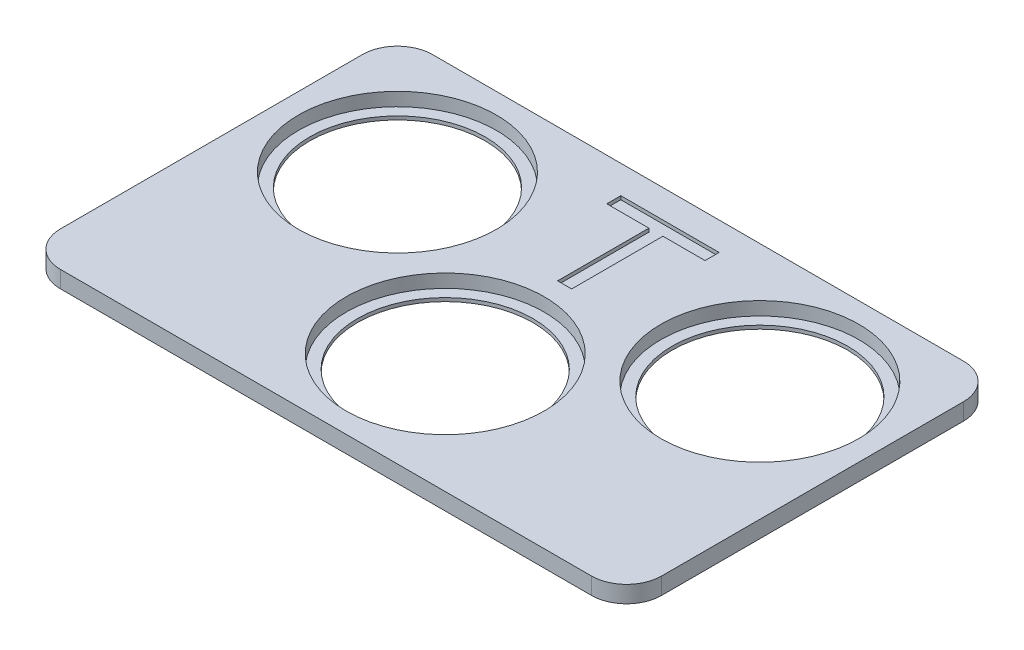
SolidWorks part; units mm, degrees
ref_plane "Front Plane" through (0, 0, 0) normal (0, 0, 1) x (1, 0, 0)
ref_plane "Top Plane" through (0, 0, 0) normal (0, 1, 0) x (1, 0, 0)
ref_plane "Right Plane" through (0, 0, 0) normal (1, 0, 0) x (0, 0, -1)
sketch "Sketch1" plane through (0, 0, 0) normal (0, 1, 0) x (1, 0, 0)
  line L1 (-42.8, 26.49) -> (42.8, 26.49)
  line L2 (-42.8, 26.49) -> (-42.8, -26.49)
  line L3 (-42.8, -26.49) -> (42.8, -26.49)
  line L4 (42.8, 26.49) -> (42.8, -26.49)
  line L5 (-42.8, 26.49) -> (42.8, -26.49) construction
  line L6 (-42.8, -26.49) -> (42.8, 26.49) construction
  point P0 (0, 0)
  dimension "D1" = 85.6
  dimension "D2" = 52.98
extrude "Boss-Extrude1" add sketch "Sketch1" along normal blind 2.4
sketch "Sketch2" plane through (0, 2.4, 0) normal (0, 1, 0) x (1, 0, 0)
  line L0 (-42.8, 26.49) -> (-42.8, -26.49) construction
  line L1 (42.8, 26.49) -> (-42.8, 26.49) construction
  line L2 (42.8, -26.49) -> (42.8, 26.49) construction
  circle A0 centre (-25.8, 9.49) radius 14.1
  circle A1 centre (0, -9.51) radius 14.1
  circle A2 centre (25.8, 9.49) radius 14.1
  dimension "D1" = 28.2
  dimension "D2" = 28.2
  dimension "D3" = 28.2
  dimension "D4" = 17
  dimension "D5" = 17
  dimension "D6" = 17
  dimension "D7" = 19
extrude "Cut-Extrude1" cut sketch "Sketch2" against normal blind 1.9
sketch "Sketch3" plane through (0, 0.5, 0) normal (0, 1, 0) x (1, 0, 0)
  circle A0 centre (-25.8, 9.49) radius 12.5
  circle A1 centre (0, -9.51) radius 12.5
  circle A2 centre (25.8, 9.49) radius 12.5
  dimension "D1" = 25
  dimension "D2" = 25
  dimension "D3" = 25
extrude "Cut-Extrude2" cut sketch "Sketch3" against normal blind 1.75
fillet "Fillet1" radius 5 4 edges at (42.8, 1.2, -26.49) (42.8, 1.2, 26.49) (-42.8, 1.2, 26.49) (-42.8, 1.2, -26.49)
sketch "Sketch4" plane through (0, 2.4, 0) normal (0, 1, 0) x (1, 0, 0)
  line L0 (-1, 20.49) -> (-1, 7.49)
  line L1 (-1, 21.49) -> (1, 21.49)
  line L2 (-1, 21.49) -> (-1, 21.3471)
  line L3 (-1, 7.49) -> (1, 7.49)
  line L4 (1, 21.49) -> (1, 21.3471)
  line L5 (-1, 21.49) -> (-0.98, 21.35) construction
  line L6 (-1, 7.49) -> (0.8571, 20.49) construction
  line L7 (-7, 22.49) -> (7, 22.49)
  line L8 (-7, 22.49) -> (-7, 20.49)
  line L9 (-7, 20.49) -> (-0.8571, 20.49)
  line L10 (7, 22.49) -> (7, 20.49)
  line L11 (-7, 22.49) -> (7, 20.49) construction
  line L12 (-7, 20.49) -> (7, 22.49) construction
  line L13 (-0.8571, 20.49) -> (1, 7.49) construction
  line L14 (0.98, 21.35) -> (1, 21.49) construction
  line L15 (1, 20.49) -> (1, 7.49)
  line L16 (0.8571, 20.49) -> (7, 20.49)
  circle A0 centre (0, -9.51) radius 14.1 construction
  point P0 (0, 14.49)
  point P8 (0, 21.49)
  point P21 (0, 0)
  dimension "D1" = 2
  dimension "D2" = 17
  dimension "D3" = 14
  dimension "D4" = 14
  dimension "D5" = 2
extrude "Cut-Extrude3" cut sketch "Sketch4" against normal blind 0.5 and the other way through all
equation "\"D6@Sketch2\"=\"D4@Sketch2\""
equation "\"D2@Sketch2\"=\"D1@Sketch2\""
equation "\"D3@Sketch2\"=\"D1@Sketch2\""
